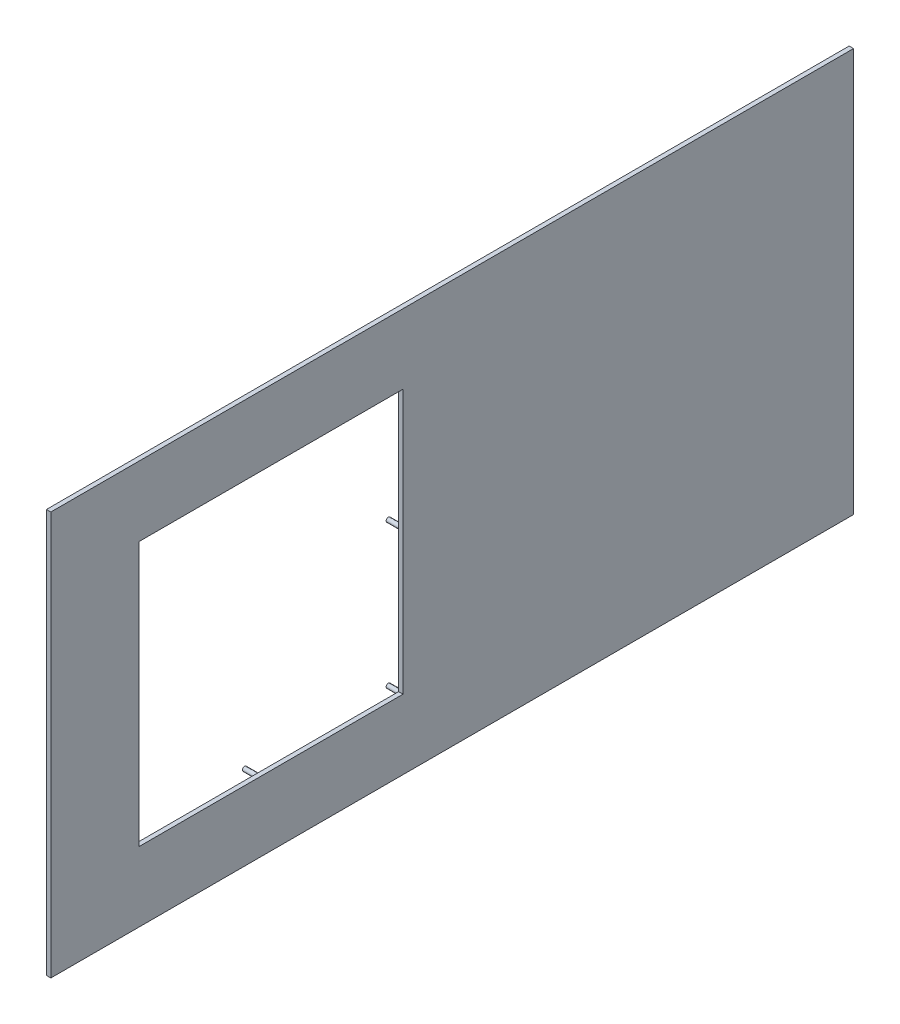
SolidWorks part; units mm, degrees
material "ASTM A36 Steel"
ref_plane "Front Plane" through (0, 0, 0) normal (0, 0, 1) x (1, 0, 0)
ref_plane "Top Plane" through (0, 0, 0) normal (0, 1, 0) x (1, 0, 0)
ref_plane "Right Plane" through (0, 0, 0) normal (1, 0, 0) x (0, 0, -1)
sketch "Sketch1" plane through (0, 0, 0) normal (1, 0, 0) x (0, 0, -1)
  line L1 (-273.5, -137.5) -> (273.5, -137.5)
  line L2 (-273.5, -137.5) -> (-273.5, 137.5)
  line L3 (-273.5, 137.5) -> (273.5, 137.5)
  line L4 (273.5, -137.5) -> (273.5, 137.5)
  line L5 (-273.5, -137.5) -> (273.5, 137.5) construction
  line L6 (-273.5, 137.5) -> (273.5, -137.5) construction
  point P0 (0, 0)
  dimension "D1" = 275
  dimension "D2" = 547
extrude "Boss-Extrude1" add sketch "Sketch1" along normal blind 3
sketch "Sketch2" plane through (3, 0, 0) normal (1, 0, 0) x (0, 0, -1)
  line L0 (-273.5, -137.5) -> (273.5, -137.5) construction
  line L1 (-213.5, -90) -> (-33.5, -90)
  line L2 (-213.5, -90) -> (-213.5, 90)
  line L3 (-213.5, 90) -> (-33.5, 90)
  line L4 (-33.5, -90) -> (-33.5, 90)
  line L5 (-273.5, 137.5) -> (-273.5, -137.5) construction
  dimension "D1" = 180
  dimension "D2" = 180
  dimension "D3" = 47.5
  dimension "D4" = 60
extrude "Cut-Extrude1" cut sketch "Sketch2" against normal blind 3
sketch "Sketch3" plane through (0, 0, 0) normal (-1, 0, 0) x (0, 0, 1)
  line L0 (213.5, -90) -> (33.5, -90) construction
  line L1 (221.5, 98) -> (25.5, 98) construction
  line L2 (221.5, 98) -> (221.5, -98) construction
  line L3 (221.5, -98) -> (25.5, -98) construction
  line L4 (25.5, 98) -> (25.5, -98) construction
  line L5 (213.5, 90) -> (213.5, -90) construction
  circle A0 centre (25.5, 98) radius 1.5
  circle A1 centre (221.5, -98) radius 1.5
  circle A2 centre (123.5, 98) radius 1.5
  circle A3 centre (221.5, 98) radius 1.5
  circle A4 centre (123.5, -98) radius 1.5
  circle A5 centre (25.5, -98) radius 1.5
  circle A6 centre (25.5, 0) radius 1.5
  circle A7 centre (221.5, 0) radius 1.5
  dimension "D4" = 3
  dimension "D1" = 196
  dimension "D2" = 8
  dimension "D3" = 8
extrude "Boss-Extrude2" add sketch "Sketch3" along normal blind 15
